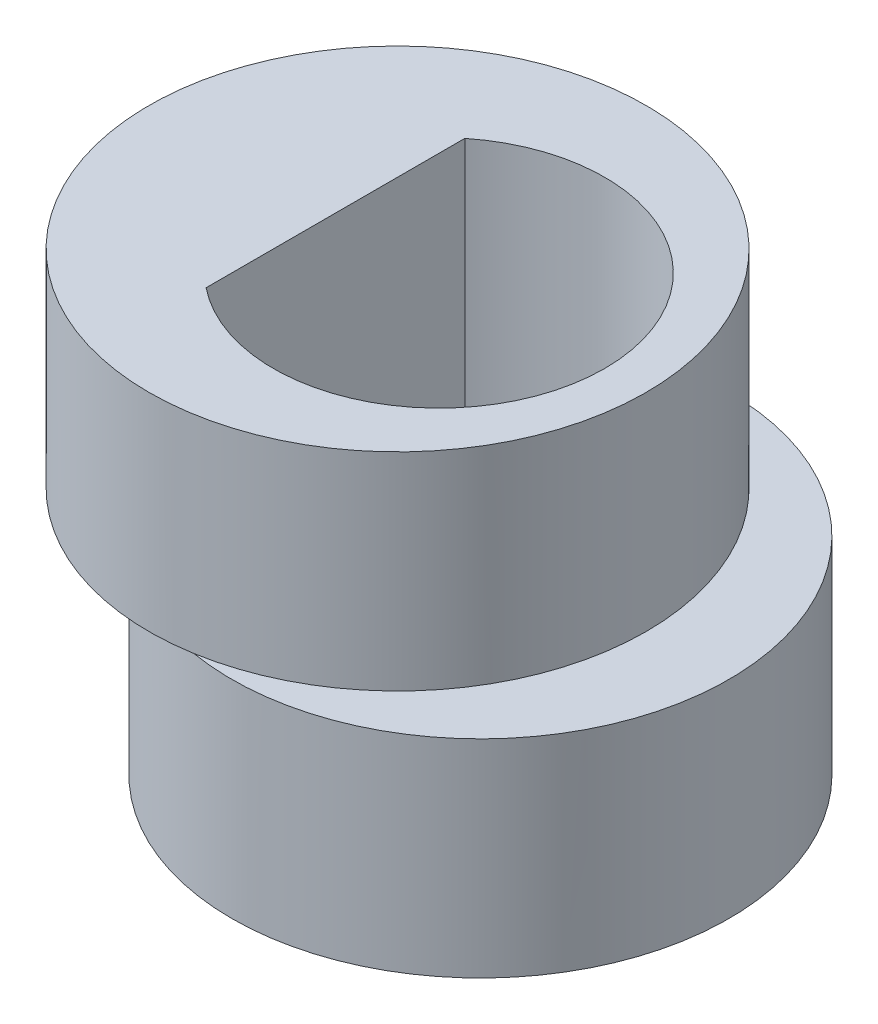
SolidWorks part; units mm, degrees
ref_plane "Front Plane" through (0, 0, 0) normal (0, 0, 1) x (1, 0, 0)
ref_plane "Top Plane" through (0, 0, 0) normal (0, 1, 0) x (1, 0, 0)
ref_plane "Right Plane" through (0, 0, 0) normal (1, 0, 0) x (0, 0, -1)
sketch "Sketch1" plane through (0, 0, 0) normal (0, 1, 0) x (1, 0, 0)
  line L0 (0, 0) -> (-5882.8967, 0) construction
  line L1 (0, 0) -> (0, -5882.8967) construction
  circle A0 centre (0, 0) radius 4
  circle A1 centre (1, 0) radius 6
  dimension "D1" = 8
  dimension "D2" = 12
  dimension "D3" = 1
extrude "Boss-Extrude1" add sketch "Sketch1" along normal blind 5
sketch "Sketch2" plane through (0, 5, 0) normal (0, 1, 0) x (1, 0, 0)
  line L0 (0, 0) -> (-50000, 0) construction
  line L1 (0, 0) -> (0, -50000) construction
  circle A0 centre (0, 0) radius 4
  circle A1 centre (-1, 0) radius 6
  dimension "D1" = 8
  dimension "D2" = 12
  dimension "D3" = 1
extrude "Boss-Extrude2" add sketch "Sketch2" along normal blind 5
sketch "Sketch3" plane through (0, 0, 0) normal (0, 1, 0) x (1, 0, 0)
  line L0 (0, 0) -> (-50000, 0) construction
  line L1 (0, 0) -> (0, -50000) construction
  line L2 (-2.5, 3.1225) -> (-2.5, -3.1225)
  arc A0 (-2.5, 3.1225) -> (-2.5, -3.1225) centre (0, 0) ccw
  dimension "D1" = 8
  dimension "D2" = 2.5
extrude "Boss-Extrude3" add sketch "Sketch3" along normal blind 10
